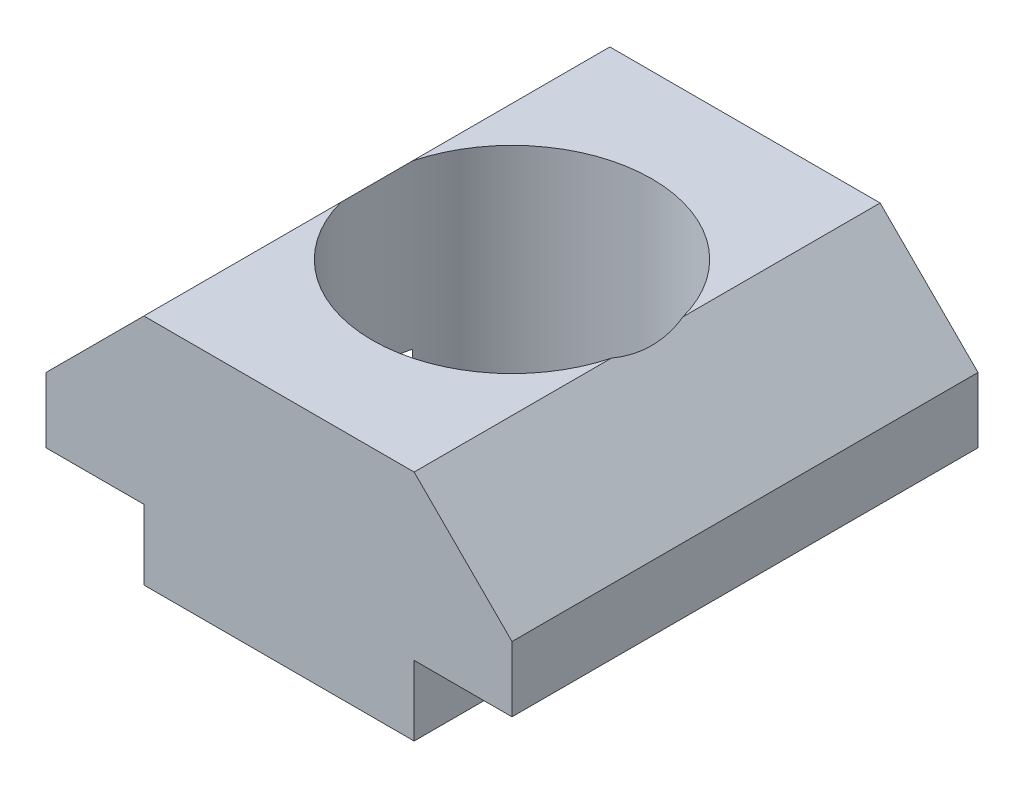
SolidWorks part; units mm, degrees
ref_plane "前视基准面" through (0, 0, 0) normal (0, 0, 1) x (1, 0, 0)
ref_plane "上视基准面" through (0, 0, 0) normal (0, 1, 0) x (1, 0, 0)
ref_plane "右视基准面" through (0, 0, 0) normal (1, 0, 0) x (0, 0, -1)
sketch "草图1" plane through (0, 0, 0) normal (0, 0, 1) x (1, 0, 0)
  line L0 (-2.9, 0) -> (2.9, 0)
  line L1 (2.9, 0) -> (2.9, 1.5)
  line L2 (2.9, 1.5) -> (5, 1.5)
  line L3 (5, 1.5) -> (5, 2.9)
  line L4 (5, 2.9) -> (2.9, 5)
  line L5 (2.9, 5) -> (-2.9, 5)
  line L6 (-2.9, 5) -> (-5, 2.9)
  line L7 (-5, 2.9) -> (-5, 1.5)
  line L8 (-5, 1.5) -> (-2.9, 1.5)
  line L9 (-2.9, 1.5) -> (-2.9, 0)
  line L10 (0, -82.6522) -> (0, 4049.9602) construction
  point P14 (0, 0)
  point P17 (-5, 2.2)
  dimension "D1" = 5.8
  dimension "D2" = 5
  dimension "D3" = 10
  dimension "D4" = 135
  dimension "D5" = 1.5
extrude "凸台-拉伸1" add sketch "草图1" against normal blind 10
sketch "草图4" plane through (0, 5, 0) normal (0, 1, 0) x (1, 0, 0)
  line L0 (0, -990) -> (0, 49010) construction
  line L1 (2.9, 10) -> (-2.9, 10) construction
  line L2 (-995.1, 5) -> (49004.9, 5) construction
  line L3 (5, 10) -> (5, 0) construction
  circle A0 centre (0, 5) radius 3
  point P5 (0, 10)
  point P10 (5, 5)
  dimension "D1" = 6
extrude "切除-拉伸1" cut sketch "草图4" against normal through all
